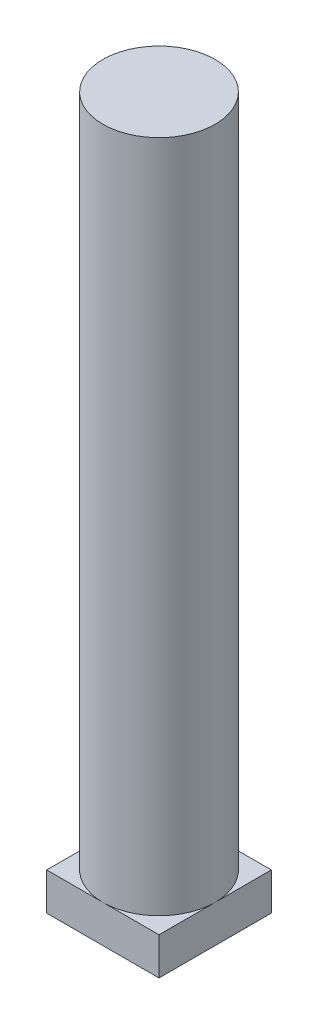
SolidWorks part; units mm, degrees
material "AISI 1045 Steel, cold drawn"
ref_plane "Front Plane" through (0, 0, 0) normal (0, 0, 1) x (1, 0, 0)
ref_plane "Top Plane" through (0, 0, 0) normal (0, 1, 0) x (1, 0, 0)
ref_plane "Right Plane" through (0, 0, 0) normal (1, 0, 0) x (0, 0, -1)
sketch "Sketch1" plane through (0, 0, 0) normal (0, 1, 0) x (1, 0, 0)
  line L1 (0, 0) -> (30, 0)
  line L2 (0, 0) -> (0, -30)
  line L3 (0, -30) -> (30, -30)
  line L4 (30, 0) -> (30, -30)
  dimension "D1" = 30
  dimension "D2" = 30
extrude "Boss-Extrude1" add sketch "Sketch1" along normal blind 10
sketch "Sketch2" plane through (0, 10, 0) normal (0, 1, 0) x (1, 0, 0)
  line L0 (0, -30) -> (30, -30) construction
  line L1 (30, -30) -> (30, 0) construction
  circle A0 centre (15, -15) radius 15
  dimension "D1" = 30
  dimension "D2" = 15
  dimension "D3" = 15
extrude "Boss-Extrude2" add sketch "Sketch2" along normal blind 180
